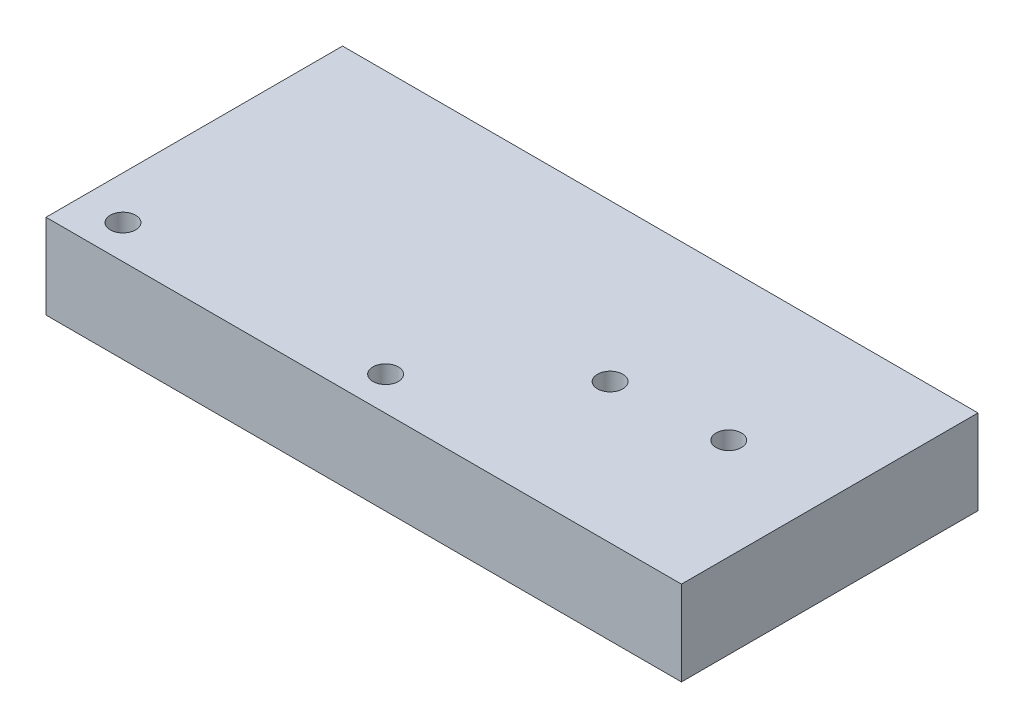
SolidWorks part; units mm, degrees
ref_plane "Front Plane" through (0, 0, 0) normal (0, 0, 1) x (1, 0, 0)
ref_plane "Top Plane" through (0, 0, 0) normal (0, 1, 0) x (1, 0, 0)
ref_plane "Right Plane" through (0, 0, 0) normal (1, 0, 0) x (0, 0, -1)
sketch "Sketch1" plane through (0, 0, 0) normal (0, 1, 0) x (1, 0, 0)
  line L1 (75, 35) -> (-75, 35)
  line L2 (75, 35) -> (75, -35)
  line L3 (75, -35) -> (-75, -35)
  line L4 (-75, 35) -> (-75, -35)
  point P0 (0, 0)
  dimension "D1" = 150
  dimension "D2" = 70
extrude "Boss-Extrude1" add sketch "Sketch1" along normal mid plane 20
sketch "Sketch2" plane through (0, 10, 0) normal (0, 1, 0) x (1, 0, 0)
  line L0 (-2.8306, -27) -> (59.3938, -27) construction
  line L1 (25.1694, -2) -> (25.1694, -21.3948) construction
  line L2 (25.1694, -2) -> (-2.1574, -2) construction
  line L5 (51.1694, -18.8914) -> (51.1694, 0) construction
  line L6 (51.1694, 0) -> (50.5279, 0) construction
  circle A0 centre (-64.8306, -27) radius 3
  circle A1 centre (-2.8306, -27) radius 3
  circle A2 centre (25.1694, -2) radius 3
  circle A3 centre (51.1694, 0) radius 3
  dimension "D1" = 62
  dimension "D2" = 25
  dimension "D3" = 28
  dimension "D4" = 27
  dimension "D5" = 54
extrude "Cut-Extrude1" cut sketch "Sketch2" against normal through all
